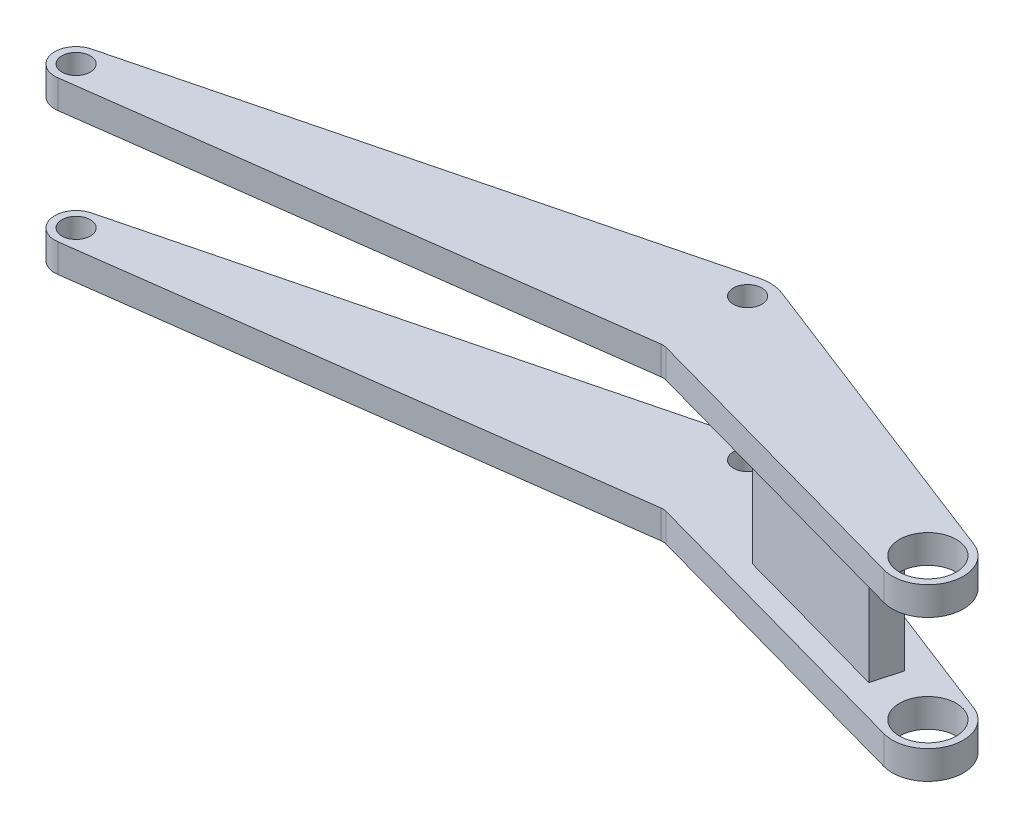
SolidWorks part; units mm, degrees
ref_plane "Front Plane" through (0, 0, 0) normal (0, 0, 1) x (1, 0, 0)
ref_plane "Top Plane" through (0, 0, 0) normal (0, 1, 0) x (1, 0, 0)
ref_plane "Right Plane" through (0, 0, 0) normal (1, 0, 0) x (0, 0, -1)
sketch "Sketch1" plane through (0, 0, 0) normal (0, 1, 0) x (1, 0, 0)
  line L0 (-63.6672, 7.2686) -> (123.7911, 54.9475)
  line L1 (132.3004, 54.4337) -> (242.6979, 11.6556)
  line L2 (-60.8269, -7.4342) -> (126.581, 17.5623)
  line L3 (128.5782, 17.4243) -> (234.841, -12.0454)
  arc A0 (-63.6672, 7.2686) -> (-60.8269, -7.4342) centre (-61.8185, 0) ccw
  arc A1 (234.841, -12.0454) -> (242.6979, 11.6556) centre (238.1815, 0) ccw
  arc A2 (132.3004, 54.4337) -> (123.7911, 54.9475) centre (127.242, 41.3794) ccw
  arc A3 (128.5782, 17.4243) -> (126.581, 17.5623) centre (127.242, 12.6062) ccw
  dimension "D1" = 15
  dimension "D2" = 25
  dimension "D4" = 10
  dimension "D5" = 28
  dimension "D3" = 300
extrude "Boss-Extrude3" add sketch "Sketch1" along normal blind 60
ref_plane "Plane1" through (0, 30, 0) normal (0, 1, 0) x (1, 0, 0)
sketch "Sketch4" plane through (0, 30, 0) normal (0, 1, 0) x (1, 0, 0)
  circle A0 centre (238.1815, 0) radius 10
  circle A2 centre (-61.8185, 0) radius 5
  dimension "D1" = 20
  dimension "D2" = 10
extrude "Cut-Extrude2" cut sketch "Sketch4" against normal mid plane 197
sketch "Sketch5" plane through (0, 30, 0) normal (0, 1, 0) x (1, 0, 0)
  line L0 (159.7402, 16.6334) -> (216.4698, 0.9007)
  line L1 (216.4698, 0.9007) -> (219.1991, 10.7418)
  line L2 (219.1991, 10.7418) -> (164.0344, 32.1176)
  line L3 (164.0344, 32.1176) -> (159.7402, 16.6334)
  line L5 (-98.5063, 87.4299) -> (278.5997, 87.4299)
  line L6 (-98.5063, 87.4299) -> (-98.5063, -38.0217)
  line L7 (-98.5063, -38.0217) -> (278.5997, -38.0217)
  line L8 (278.5997, 87.4299) -> (278.5997, -38.0217)
  line L9 (-98.5063, 87.4299) -> (278.5997, -38.0217) construction
  line L10 (-98.5063, -38.0217) -> (278.5997, 87.4299) construction
  point P2 (90.0467, 24.7041)
extrude "Cut-Extrude3" cut sketch "Sketch5" against normal mid plane 40
sketch "Sketch6" plane through (0, 30, 0) normal (0, 1, 0) x (1, 0, 0)
  circle A0 centre (127.242, 47.4411) radius 5
  dimension "D1" = 10
extrude "Cut-Extrude4" cut sketch "Sketch6" against normal mid plane 81
